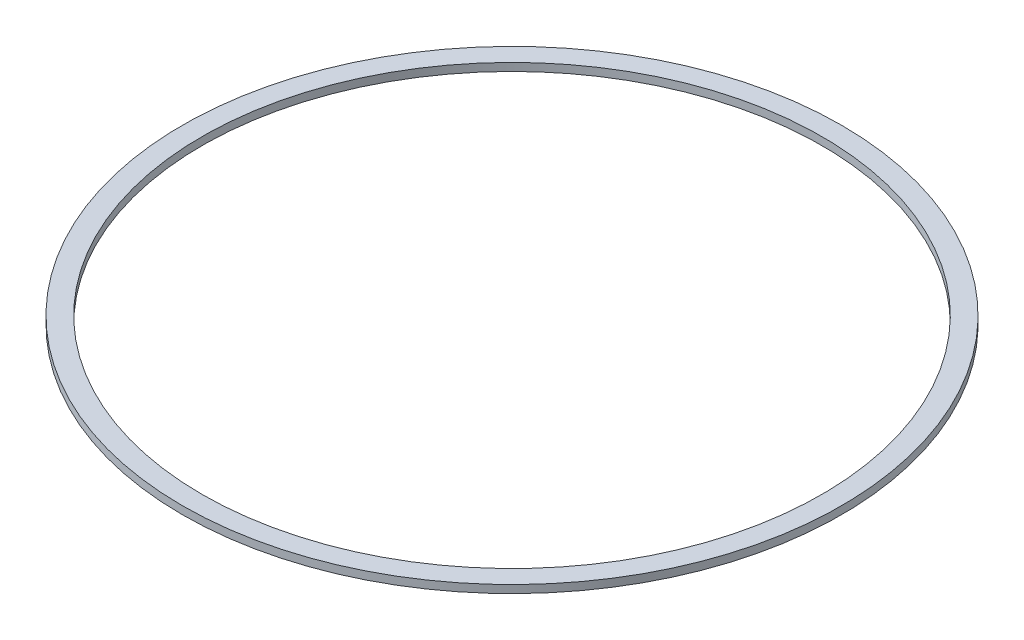
SolidWorks part; units mm, degrees
ref_plane "Front Plane" through (0, 0, 0) normal (0, 0, 1) x (1, 0, 0)
ref_plane "Top Plane" through (0, 0, 0) normal (0, 1, 0) x (1, 0, 0)
ref_plane "Right Plane" through (0, 0, 0) normal (1, 0, 0) x (0, 0, -1)
sketch "Sketch1" plane through (0, 0, 0) normal (0, 1, 0) x (1, 0, 0)
  circle A0 centre (0, 0) radius 39.5
  circle A1 centre (0, 0) radius 42
  dimension "D1" = 84
  dimension "D2" = 79
extrude "Boss-Extrude1" add sketch "Sketch1" along normal blind 1
